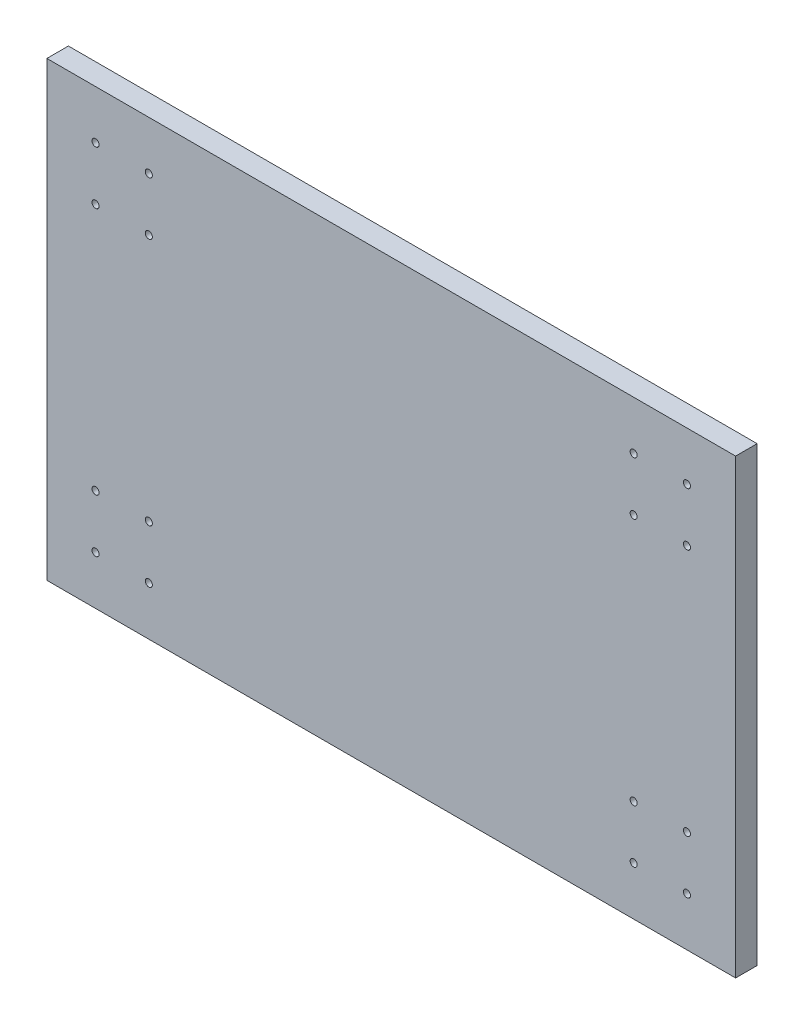
SolidWorks part; units mm, degrees
material "Д16Т ГОСТ 4784-74"
ref_plane "Спереди" through (0, 0, 0) normal (0, 0, 1) x (1, 0, 0)
ref_plane "Сверху" through (0, 0, 0) normal (0, 1, 0) x (1, 0, 0)
ref_plane "Справа" through (0, 0, 0) normal (1, 0, 0) x (0, 0, -1)
sketch "Эскиз1" plane through (0, 0, 0) normal (0, 0, 1) x (1, 0, 0)
  line L1 (0, 0) -> (320, 0)
  line L2 (0, 0) -> (0, 210)
  line L3 (0, 210) -> (320, 210)
  line L4 (320, 0) -> (320, 210)
  dimension "D1" = 210
  dimension "D2" = 320
extrude "Бобышка-Вытянуть1" add sketch "Эскиз1" along normal blind 10
hole_wizard "Отверстие обработанное метчиком M41" positions "Эскиз3" profile "Эскиз2" tap size "M4" standard "DIN"
sketch "Эскиз3" plane through (0, 0, 0) normal (0, 0, -1) x (-1, 0, 0)
  line L1 (-22.6256, 22.6256) -> (-47.3744, 22.6256)
  line L2 (-22.6256, 22.6256) -> (-22.6256, 47.3744)
  line L3 (-22.6256, 47.3744) -> (-47.3744, 47.3744)
  line L4 (-47.3744, 22.6256) -> (-47.3744, 47.3744)
  line L5 (0, 210) -> (0, 0) construction
  line L6 (0, 0) -> (-320, 0) construction
  line L7 (-160, 210) -> (-160, 0) construction
  line L8 (-320, 210) -> (0, 210) construction
  line L10 (0, 105) -> (-320, 105) construction
  line L11 (-320, 0) -> (-320, 210) construction
  line L13 (-272.6256, 22.6256) -> (-272.6256, 47.3744)
  line L14 (-297.3744, 47.3744) -> (-272.6256, 47.3744)
  line L15 (-297.3744, 22.6256) -> (-297.3744, 47.3744)
  line L16 (-297.3744, 22.6256) -> (-272.6256, 22.6256)
  line L17 (-47.3744, 187.3744) -> (-47.3744, 162.6256)
  line L18 (-22.6256, 162.6256) -> (-47.3744, 162.6256)
  line L19 (-22.6256, 187.3744) -> (-22.6256, 162.6256)
  line L20 (-22.6256, 187.3744) -> (-47.3744, 187.3744)
  line L21 (-297.3744, 187.3744) -> (-272.6256, 187.3744)
  line L22 (-297.3744, 187.3744) -> (-297.3744, 162.6256)
  line L23 (-297.3744, 162.6256) -> (-272.6256, 162.6256)
  line L24 (-272.6256, 187.3744) -> (-272.6256, 162.6256)
  circle A0 centre (-35, 35) radius 17.5
  circle A3 centre (-35, 35) radius 6
  circle A4 centre (-285, 35) radius 6
  circle A5 centre (-285, 35) radius 17.5
  circle A6 centre (-35, 175) radius 6
  circle A7 centre (-35, 175) radius 17.5
  circle A8 centre (-285, 175) radius 17.5
  circle A9 centre (-285, 175) radius 6
  point P0 (-22.6256, 22.6256)
  point P86 (-47.3744, 22.6256)
  point P88 (-47.3744, 47.3744)
  point P90 (-22.6256, 47.3744)
  point P124 (-297.3744, 47.3744)
  point P125 (-272.6256, 47.3744)
  point P126 (-272.6256, 22.6256)
  point P127 (-297.3744, 22.6256)
  point P135 (-22.6256, 162.6256)
  point P136 (-47.3744, 162.6256)
  point P137 (-47.3744, 187.3744)
  point P138 (-22.6256, 187.3744)
  point P142 (-297.3744, 187.3744)
  point P143 (-272.6256, 187.3744)
  point P144 (-272.6256, 162.6256)
  point P145 (-297.3744, 162.6256)
  dimension "D1" = 12
  dimension "D2" = 35
  dimension "D3" = 35
  dimension "D4" = 35
sketch "Эскиз2" plane through (22.6256, 22.6256, 0) normal (1, 0, 0) x (0, 1, 0)
  line L0 (0, 0) -> (0, 12.4914)
  line L1 (0, 12.4914) -> (1.65, 11.5)
  line L2 (1.65, 11.5) -> (1.65, 0.2165)
  line L3 (1.65, 0.2165) -> (2.025, 0)
  line L5 (2.025, 0) -> (0, 0)
  line L6 (-1.65, 0.2165) -> (-2.025, 0) construction
  line L10 (0, 12.4914) -> (-1.65, 11.5) construction
  line L11 (0, -6.35) -> (0, 107.95) construction
  dimension "Диаметр сверла" = 3.3
  dimension "Глубина сверла" = 11.5
  dimension "Диаметр передней зенковки" = 4.05
  dimension "Угол передней зенковки" = 120
  dimension "Угол заточки сверла" = 118
cosmetic thread "Отверстие резьбы1" parameters "D1"=8, "D2"=4
cosmetic thread "Отверстие резьбы2" parameters "D1"=8, "D2"=4
cosmetic thread "Отверстие резьбы3" parameters "D1"=8, "D2"=4
cosmetic thread "Отверстие резьбы4" parameters "D1"=8, "D2"=4
cosmetic thread "Отверстие резьбы5" parameters "D1"=8, "D2"=4
cosmetic thread "Отверстие резьбы6" parameters "D1"=8, "D2"=4
cosmetic thread "Отверстие резьбы7" parameters "D1"=8, "D2"=4
cosmetic thread "Отверстие резьбы8" parameters "D1"=8, "D2"=4
cosmetic thread "Отверстие резьбы9" parameters "D1"=8, "D2"=4
cosmetic thread "Отверстие резьбы10" parameters "D1"=8, "D2"=4
cosmetic thread "Отверстие резьбы11" parameters "D1"=8, "D2"=4
cosmetic thread "Отверстие резьбы12" parameters "D1"=8, "D2"=4
cosmetic thread "Отверстие резьбы13" parameters "D1"=8, "D2"=4
cosmetic thread "Отверстие резьбы14" parameters "D1"=8, "D2"=4
cosmetic thread "Отверстие резьбы15" parameters "D1"=8, "D2"=4
cosmetic thread "Отверстие резьбы16" parameters "D1"=8, "D2"=4
